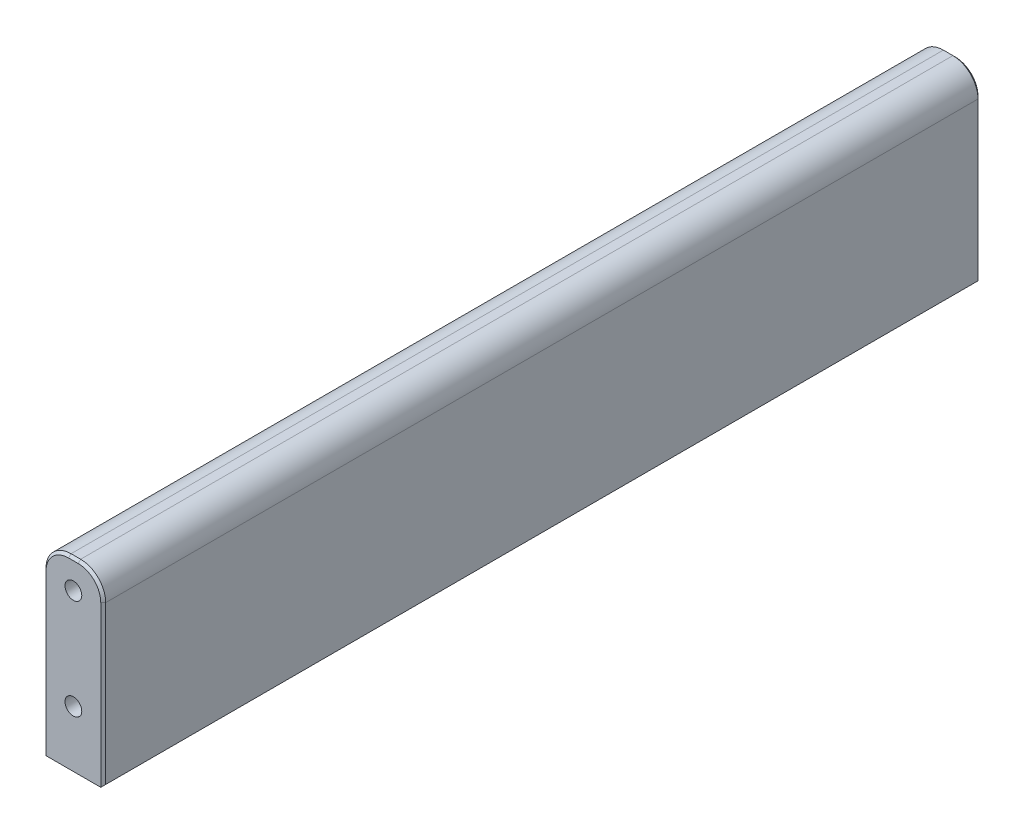
SolidWorks part; units mm, degrees
ref_plane "Front Plane" through (0, 0, 0) normal (0, 0, 1) x (1, 0, 0)
ref_plane "Top Plane" through (0, 0, 0) normal (0, 1, 0) x (1, 0, 0)
ref_plane "Right Plane" through (0, 0, 0) normal (1, 0, 0) x (0, 0, -1)
sketch "Sketch1" plane through (0, 0, 0) normal (0, 0, 1) x (1, 0, 0)
  line L1 (-0.97, 18.75) -> (0.97, 18.75)
  line L2 (-6.05, 13.67) -> (-6.05, -18.75)
  line L3 (-6.05, -18.75) -> (6.05, -18.75)
  line L4 (6.05, 13.67) -> (6.05, -18.75)
  line L5 (-6.05, 18.75) -> (6.05, -18.75) construction
  line L6 (-6.05, -18.75) -> (6.05, 18.75) construction
  arc A0 (6.05, 13.67) -> (0.97, 18.75) centre (0.97, 13.67) ccw
  arc A1 (-6.05, 13.67) -> (-0.97, 18.75) centre (-0.97, 13.67) cw
  circle A2 centre (0, 13) radius 1.7
  circle A3 centre (0, -7.32) radius 1.7
  point P0 (0, 0)
  dimension "D3" = 5.08
  dimension "D4" = 3.4
  dimension "D1" = 12.1
  dimension "D2" = 37.5
  dimension "D5" = 11.43
  dimension "D6" = 20.32
extrude "Boss-Extrude1" add sketch "Sketch1" along normal blind 177.8
chamfer "Chamfer1" distance 0.5 angle 45 12 edges at (-6.05, -2.54, 177.8) (-6.05, -2.54, 0) (-4.5621, 17.2621, 177.8) (-4.5621, 17.2621, 0) (0, 18.75, 177.8) (0, 18.75, 0) (4.5621, 17.2621, 177.8) (4.5621, 17.2621, 0) (6.05, -2.54, 177.8) (6.05, -18.75, 88.9) (6.05, -2.54, 0) (-6.05, -18.75, 88.9)
